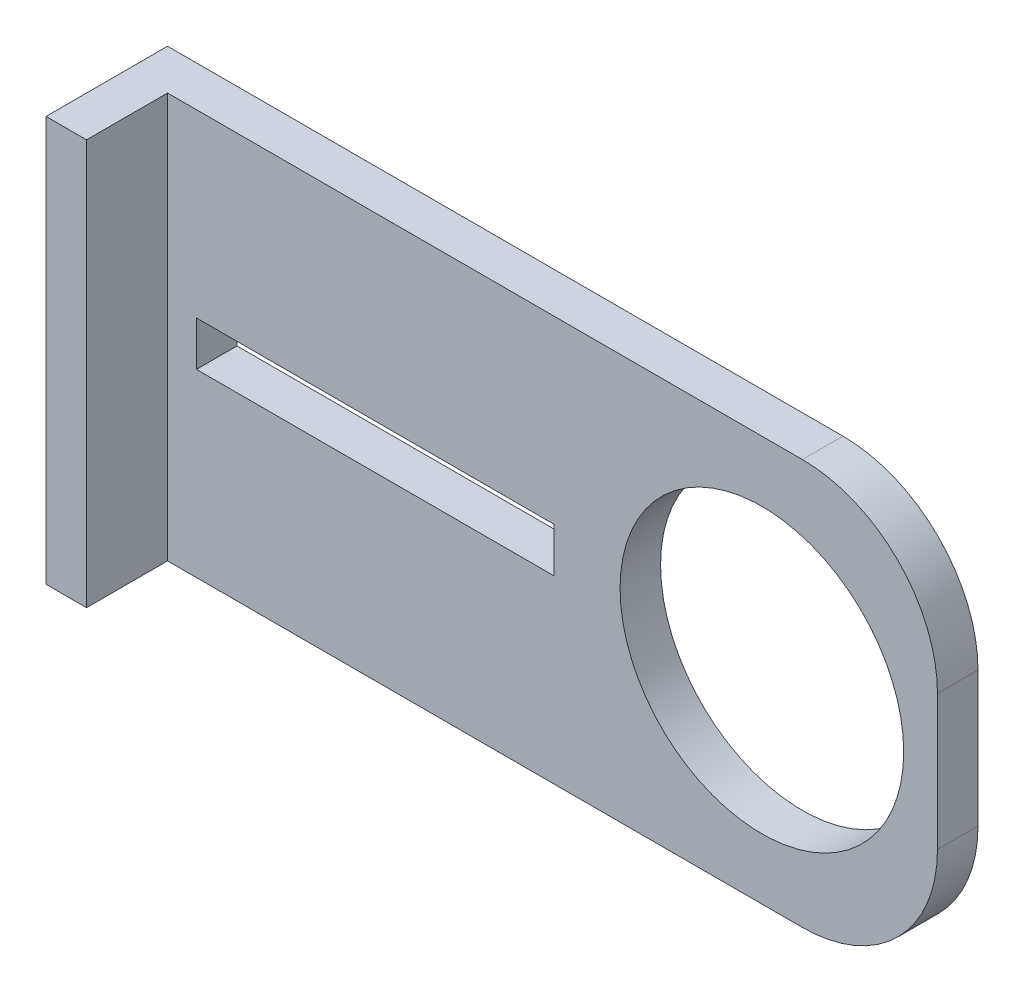
SolidWorks part; units mm, degrees
ref_plane "前视基准面" through (0, 0, 0) normal (0, 0, 1) x (1, 0, 0)
ref_plane "上视基准面" through (0, 0, 0) normal (0, 1, 0) x (1, 0, 0)
ref_plane "右视基准面" through (0, 0, 0) normal (1, 0, 0) x (0, 0, -1)
other "Configuration Table"
sketch "草图1" plane through (0, 0, 0) normal (0, 0, 1) x (1, 0, 0)
  line L1 (0, 0) -> (60, 0)
  line L2 (0, 0) -> (0, 30)
  line L3 (0, 30) -> (60, 30)
  line L4 (60, 0) -> (60, 30)
  dimension "D1" = 60
  dimension "D2" = 30
extrude "凸台-拉伸1" add sketch "草图1" along normal blind 3
sketch "草图2" plane through (0, 0, 3) normal (0, 0, 1) x (1, 0, 0)
  line L0 (60, 30) -> (0, 30) construction
  line L1 (0, 30) -> (3, 30)
  line L2 (0, 30) -> (0, 0)
  line L3 (0, 0) -> (3, 0)
  line L4 (3, 30) -> (3, 0)
  line L5 (0, 30) -> (0, 0) construction
  line L6 (0, 0) -> (60, 0) construction
  dimension "D1" = 3
extrude "凸台-拉伸2" add sketch "草图2" along normal blind 6
sketch "草图3" plane through (0, 0, 3) normal (0, 0, 1) x (1, 0, 0)
  line L0 (60, 0) -> (60, 30) construction
  circle A0 centre (47, 15) radius 10.5
  dimension "D1" = 21
  dimension "D2" = 13
extrude "切除-拉伸1" cut sketch "草图3" against normal blind 6
fillet "圆角1" radius 10 2 edges at (60, 0, 1.5) (60, 30, 1.5)
sketch "草图4" plane through (0, 0, 3) normal (0, 0, 1) x (1, 0, 0)
  line L1 (31.6051, 16.65) -> (5.141, 16.65)
  line L2 (31.6051, 16.65) -> (31.6051, 13.35)
  line L3 (31.6051, 13.35) -> (5.141, 13.35)
  line L4 (5.141, 16.65) -> (5.141, 13.35)
  line L5 (31.6051, 16.65) -> (5.141, 13.35) construction
  line L6 (31.6051, 13.35) -> (5.141, 16.65) construction
  line L9 (60, 10) -> (60, 20) construction
  point P0 (18.3731, 15)
  point P5 (0, 0)
  point P6 (0, 0)
  point P9 (16.126, 14.2428)
  point P10 (15.9334, 12.3805)
  point P11 (0, 0)
  point P12 (0, 0)
  point P13 (0, 0)
  point P14 (0, 0)
  point P15 (0, 0)
  point P16 (0, 0)
  point P21 (60, 15)
  dimension "D1" = 3.3
extrude "切除-拉伸2" cut sketch "草图4" against normal blind 6
